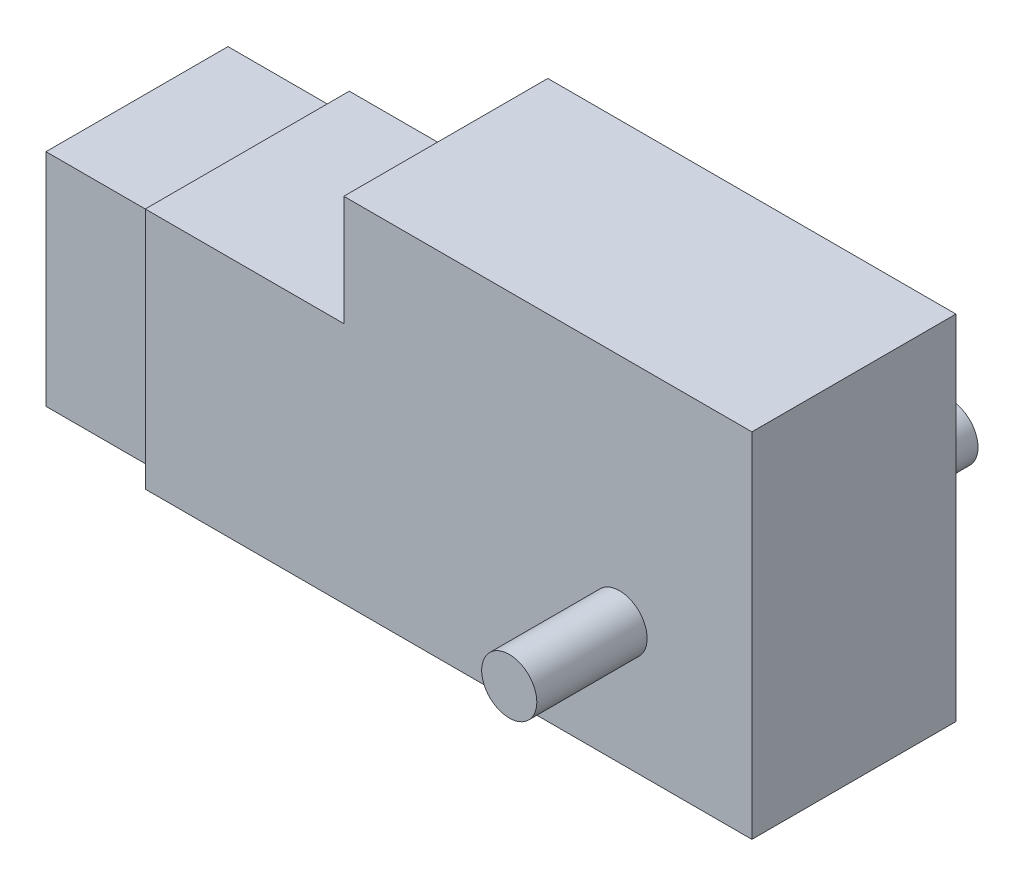
SolidWorks part; units mm, degrees
ref_plane "Front Plane" through (0, 0, 0) normal (0, 0, 1) x (1, 0, 0)
ref_plane "Top Plane" through (0, 0, 0) normal (0, 1, 0) x (1, 0, 0)
ref_plane "Right Plane" through (0, 0, 0) normal (1, 0, 0) x (0, 0, -1)
sketch "Sketch1" plane through (0, 0, 0) normal (0, 1, 0) x (1, 0, 0)
  line L1 (-27.5, -9.25) -> (27.5, -9.25)
  line L2 (-27.5, -9.25) -> (-27.5, 9.25)
  line L3 (-27.5, 9.25) -> (27.5, 9.25)
  line L4 (27.5, -9.25) -> (27.5, 9.25)
  line L5 (-27.5, -9.25) -> (27.5, 9.25) construction
  line L6 (-27.5, 9.25) -> (27.5, -9.25) construction
  point P0 (0, 0)
  dimension "D1" = 55
  dimension "D2" = 18.5
extrude "Boss-Extrude1" add sketch "Sketch1" along normal blind 22
sketch "Sketch2" plane through (-27.5, 0, 0) normal (-1, 0, 0) x (0, 0, 1)
  line L8 (-8.25, 1) -> (8.25, 1)
  line L9 (8.25, 1) -> (8.25, 21)
  line L10 (8.25, 21) -> (-8.25, 21)
  line L11 (-8.25, 21) -> (-8.25, 1)
  line L12 (-8.25, 1) -> (8.25, 1)
  line L13 (8.25, 1) -> (8.25, 21)
  line L14 (8.25, 21) -> (-8.25, 21)
  line L15 (-8.25, 21) -> (-8.25, 1)
  dimension "D1" = 1
extrude "Boss-Extrude2" add sketch "Sketch2" along normal blind 10
sketch "Sketch3" plane through (0, 0, 9.25) normal (0, 0, 1) x (1, 0, 0)
  line L0 (27.5, 11) -> (-27.5, 11) construction
  line L1 (27.5, 22) -> (27.5, 0) construction
  line L2 (-27.5, 22) -> (-27.5, 0) construction
sketch "Sketch5" plane through (0, 0, 9.25) normal (0, 0, 1) x (1, 0, 0)
  line L0 (27.5, 22) -> (27.5, 0) construction
  circle A0 centre (15.5, 11.028) radius 2.5
  dimension "D2" = 5
  dimension "D1" = 12
extrude "Boss-Extrude3" add sketch "Sketch5" along normal blind 10 and the other way blind 30
sketch "Sketch6" plane through (0, 22, 0) normal (0, 1, 0) x (1, 0, 0)
  line L0 (27.5, -9.25) -> (-27.5, -9.25) construction
  line L1 (27.5, 9.25) -> (-9.5, 9.25)
  line L2 (27.5, 9.25) -> (27.5, -9.25)
  line L3 (27.5, -9.25) -> (-9.5, -9.25)
  line L4 (-9.5, 9.25) -> (-9.5, -9.25)
  dimension "D1" = 37
extrude "Boss-Extrude4" add sketch "Sketch6" along normal blind 10
